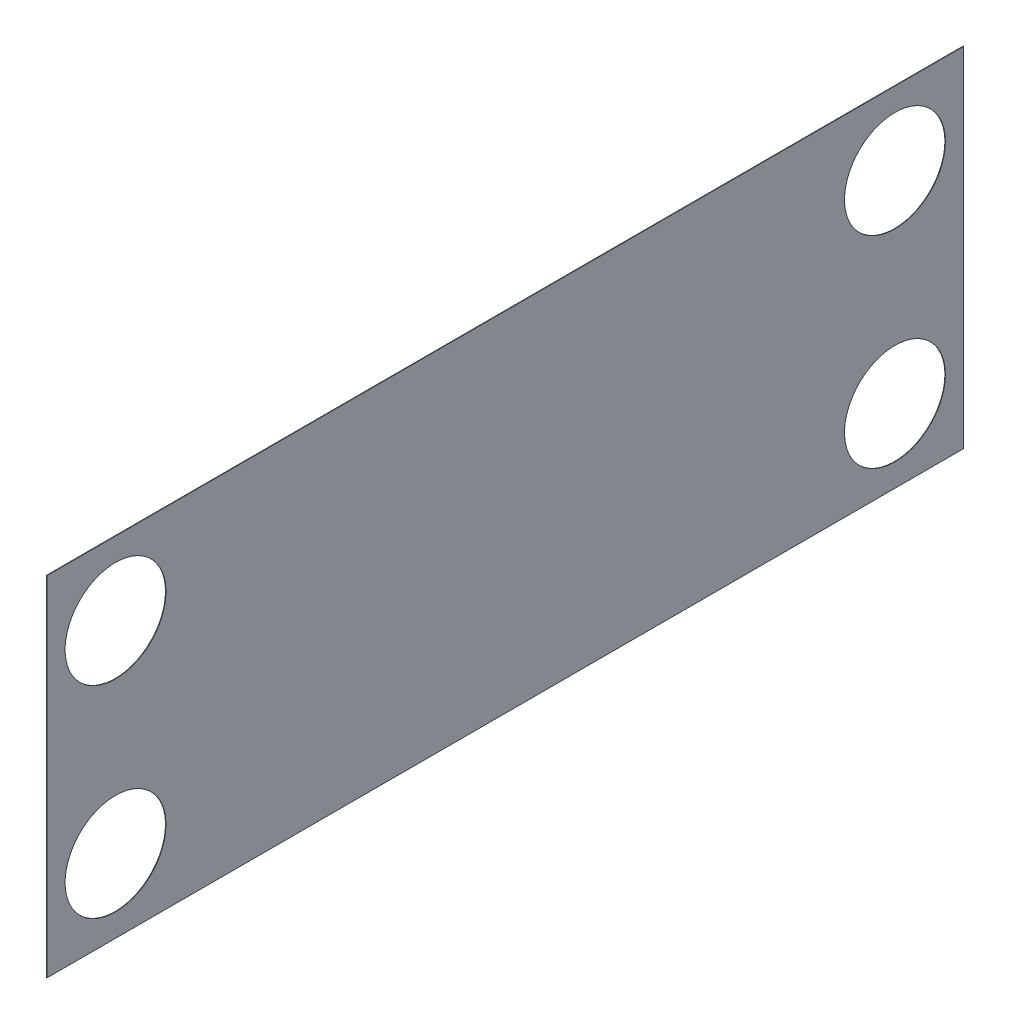
SolidWorks part; units mm, degrees
material "Low Carbon Steel"
ref_plane "Front Plane" through (0, 0, 0) normal (0, 0, 1) x (1, 0, 0)
ref_plane "Top Plane" through (0, 0, 0) normal (0, 1, 0) x (1, 0, 0)
ref_plane "Right Plane" through (0, 0, 0) normal (1, 0, 0) x (0, 0, -1)
sketch "Sketch1" plane through (0, 0, 0) normal (1, 0, 0) x (0, 0, -1)
  line L0 (50, 19) -> (-50, -19) construction
  line L1 (-50, 19) -> (50, 19)
  line L2 (-50, 19) -> (-50, -19)
  line L3 (-50, -19) -> (50, -19)
  line L4 (50, 19) -> (50, -19)
  dimension "D1" = 100
  dimension "D2" = 38
extrude "Boss-Extrude1" add sketch "Sketch1" along normal blind 0.0508
hole_wizard "M10 Clearance Hole1" positions "Sketch2" profile "Sketch3" hole size "M10" standard "Peddi DIN" end condition through all
sketch "Sketch2" plane through (0.0508, 0, 0) normal (1, 0, 0) x (0, 0, -1)
  line L0 (42.5, 11) -> (42.5, -11) construction
  line L1 (42.5, -11) -> (-42.5, 11) construction
  line L2 (-42.5, 11) -> (-42.5, -11) construction
  line L3 (-42.5, -11) -> (42.5, -11) construction
  point P0 (-42.5, 11)
  point P2 (-42.5, -11)
  point P4 (42.5, 11)
  point P6 (42.5, -11)
  dimension "D1" = 22
  dimension "D2" = 85
sketch "Sketch3" plane through (0.0508, 11, 42.5) normal (0, 1, 0) x (0, 0, -1)
  line L0 (0, 0) -> (0, 0.0508)
  line L1 (0, 0.0508) -> (5.5, 0.0508)
  line L2 (5.5, 0.0508) -> (5.5, 0)
  line L5 (5.5, 0) -> (0, 0)
  line L11 (0, -6.35) -> (0, 107.95) construction
  dimension "Thru Hole Dia." = 11
  dimension "Thru Hole Depth" = 0.0508
other "Freeze***"
